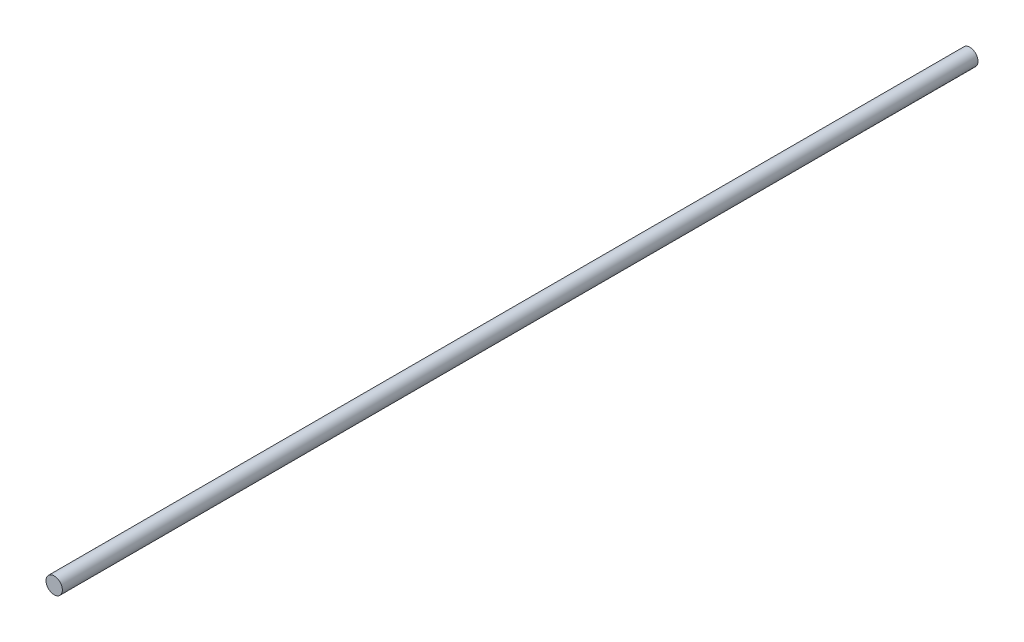
SolidWorks part; units mm, degrees
material "AISI 304"
ref_plane "Front" through (0, 0, 0) normal (0, 0, 1) x (1, 0, 0)
ref_plane "Top" through (0, 0, 0) normal (0, 1, 0) x (1, 0, 0)
ref_plane "Right" through (0, 0, 0) normal (1, 0, 0) x (0, 0, -1)
sketch "Sketch1" plane through (0, 0, 0) normal (0, 0, 1) x (1, 0, 0)
  circle A0 centre (0, 0) radius 2.5
  dimension "D1" = 5
extrude "Boss-Extrude1" add sketch "Sketch1" along normal blind 280
